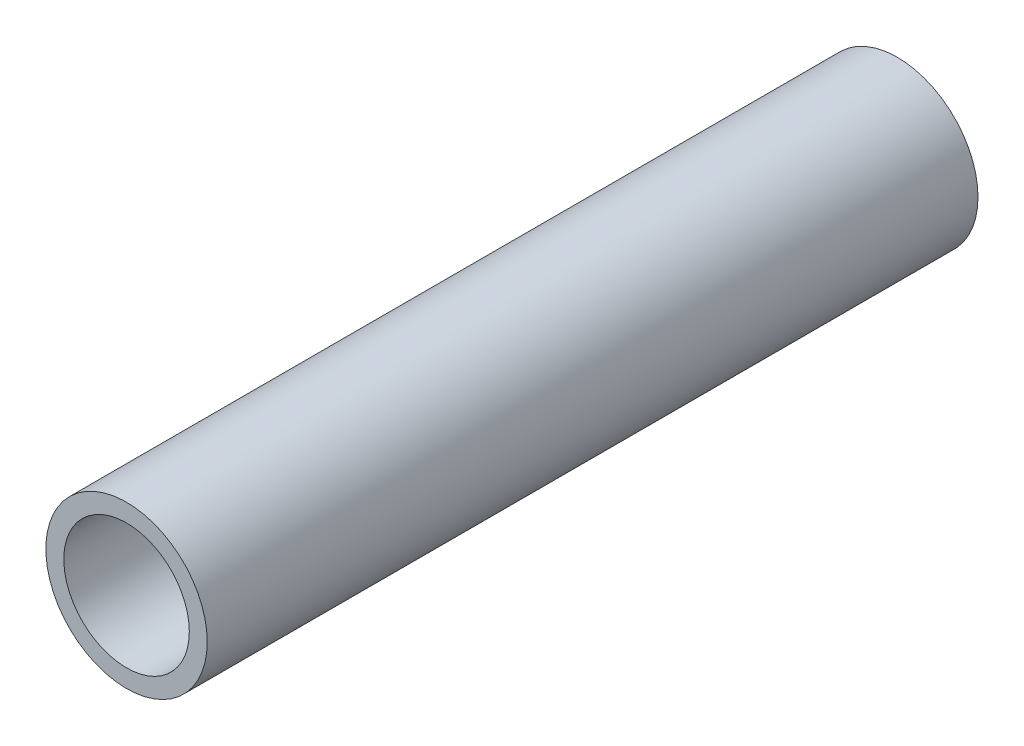
SolidWorks part; units mm, degrees
ref_plane "Front Plane" through (0, 0, 0) normal (0, 0, 1) x (1, 0, 0)
ref_plane "Top Plane" through (0, 0, 0) normal (0, 1, 0) x (1, 0, 0)
ref_plane "Right Plane" through (0, 0, 0) normal (1, 0, 0) x (0, 0, -1)
sketch "Sketch1" plane through (0, 0, 0) normal (0, 0, 1) x (1, 0, 0)
  circle A0 centre (0, 0) radius 9
  circle A1 centre (0, 0) radius 7
  dimension "D1" = 14
  dimension "D2" = 18
extrude "Boss-Extrude1" add sketch "Sketch1" along normal mid plane 85.96
